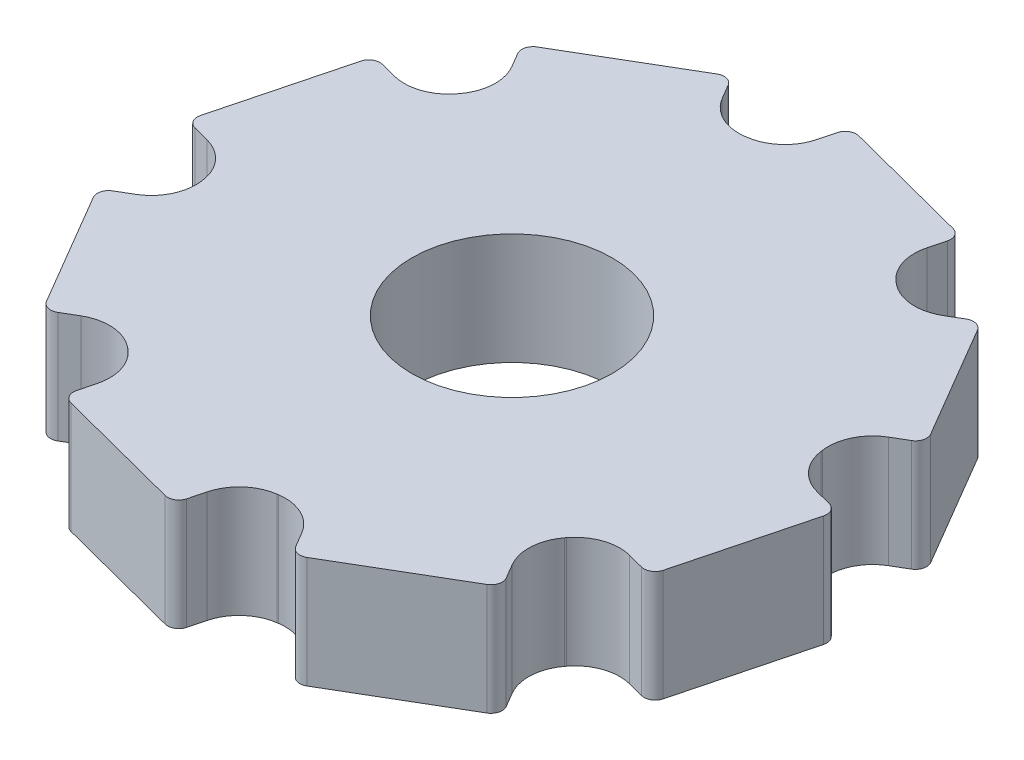
SolidWorks part; units mm, degrees
ref_plane "Спереди" through (0, 0, 0) normal (0, 0, 1) x (1, 0, 0)
ref_plane "Сверху" through (0, 0, 0) normal (0, 1, 0) x (1, 0, 0)
ref_plane "Справа" through (0, 0, 0) normal (1, 0, 0) x (0, 0, -1)
sketch "Эскиз1" plane through (0, 0, 0) normal (0, 1, 0) x (1, 0, 0)
  line L0 (-2.8067, 0.7298) -> (0, 0) construction
  line L1 (2.5044, -1.8924) -> (3.109, 0.4327) construction
  line L2 (3.109, 0.4327) -> (1.8924, 2.5044) construction
  line L3 (1.8924, 2.5044) -> (-0.4327, 3.109) construction
  line L4 (-0.4327, 3.109) -> (-2.5044, 1.8924) construction
  line L5 (-2.5044, 1.8924) -> (-3.109, -0.4327) construction
  line L6 (-3.109, -0.4327) -> (-1.8924, -2.5044) construction
  line L7 (-1.8924, -2.5044) -> (0.4327, -3.109) construction
  line L8 (0.4327, -3.109) -> (2.5044, -1.8924) construction
  line L9 (-2.9552, 0.1586) -> (-2.6581, 1.3011)
  line L10 (-2.5362, 1.3727) -> (-2.3902, 1.3347)
  line L11 (-2.8836, 0.0366) -> (-2.7376, -0.0013)
  line L12 (-0.8227, 2.764) -> (-0.7463, 2.6339)
  line L13 (-1.9775, 2.2018) -> (-0.9596, 2.7996)
  line L14 (-2.0131, 2.0649) -> (-1.9367, 1.9349)
  line L15 (1.3727, 2.5362) -> (1.3347, 2.3902)
  line L16 (0.1586, 2.9552) -> (1.3011, 2.6581)
  line L17 (0.0366, 2.8836) -> (-0.0013, 2.7376)
  line L18 (2.764, 0.8227) -> (2.6339, 0.7463)
  line L19 (2.2018, 1.9775) -> (2.7996, 0.9596)
  line L20 (2.0649, 2.0131) -> (1.9349, 1.9367)
  line L21 (2.5362, -1.3727) -> (2.3902, -1.3347)
  line L22 (2.9552, -0.1586) -> (2.6581, -1.3011)
  line L23 (2.8836, -0.0366) -> (2.7376, 0.0013)
  line L24 (0.8227, -2.764) -> (0.7463, -2.6339)
  line L25 (1.9775, -2.2018) -> (0.9596, -2.7996)
  line L26 (2.0131, -2.0649) -> (1.9367, -1.9349)
  line L27 (-1.3727, -2.5362) -> (-1.3347, -2.3902)
  line L28 (-0.1586, -2.9552) -> (-1.3011, -2.6581)
  line L29 (-0.0366, -2.8836) -> (0.0013, -2.7376)
  line L30 (-2.764, -0.8227) -> (-2.6339, -0.7463)
  line L31 (-2.2018, -1.9775) -> (-2.7996, -0.9596)
  line L32 (-2.0649, -2.0131) -> (-1.9349, -1.9367)
  arc A0 (-0.3342, 2.442) -> (-0.3454, 2.4404) centre (0, 0) ccw
  circle A1 centre (0, 0) radius 0.9
  arc A2 (-2.442, -0.3342) -> (-2.4404, -0.3454) centre (0, 0) ccw
  arc A3 (-1.9631, 1.4904) -> (-1.9699, 1.4815) centre (0, 0) ccw
  arc A4 (-1.4904, -1.9631) -> (-1.4815, -1.9699) centre (0, 0) ccw
  arc A5 (1.4904, 1.9631) -> (1.4815, 1.9699) centre (0, 0) ccw
  arc A6 (2.442, 0.3342) -> (2.4404, 0.3454) centre (0, 0) ccw
  arc A7 (1.9631, -1.4904) -> (1.9699, -1.4815) centre (0, 0) ccw
  arc A8 (0.3342, -2.442) -> (0.3454, -2.4404) centre (0, 0) ccw
  arc A9 (-1.9367, 1.9349) -> (-1.9631, 1.4904) centre (-2.2817, 1.7323) cw
  arc A10 (-1.9699, 1.4815) -> (-2.3902, 1.3347) centre (-2.2895, 1.7219) cw
  arc A11 (-2.7376, -0.0013) -> (-2.442, -0.3342) centre (-2.8383, -0.3885) cw
  arc A12 (-2.4404, -0.3454) -> (-2.6339, -0.7463) centre (-2.8365, -0.4014) cw
  arc A13 (-1.9349, -1.9367) -> (-1.4904, -1.9631) centre (-1.7323, -2.2817) cw
  arc A14 (-1.4815, -1.9699) -> (-1.3347, -2.3902) centre (-1.7219, -2.2895) cw
  arc A15 (0.0013, -2.7376) -> (0.3342, -2.442) centre (0.3885, -2.8383) cw
  arc A16 (0.3454, -2.4404) -> (0.7463, -2.6339) centre (0.4014, -2.8365) cw
  arc A17 (1.9367, -1.9349) -> (1.9631, -1.4904) centre (2.2817, -1.7323) cw
  arc A18 (1.9699, -1.4815) -> (2.3902, -1.3347) centre (2.2895, -1.7219) cw
  arc A19 (2.7376, 0.0013) -> (2.442, 0.3342) centre (2.8383, 0.3885) cw
  arc A20 (2.4404, 0.3454) -> (2.6339, 0.7463) centre (2.8365, 0.4014) cw
  arc A21 (1.9349, 1.9367) -> (1.4904, 1.9631) centre (1.7323, 2.2817) cw
  arc A22 (1.4815, 1.9699) -> (1.3347, 2.3902) centre (1.7219, 2.2895) cw
  arc A23 (-0.3342, 2.442) -> (-0.0013, 2.7376) centre (-0.3885, 2.8383) ccw
  arc A24 (-0.3454, 2.4404) -> (-0.7463, 2.6339) centre (-0.4014, 2.8365) cw
  arc A25 (0.0366, 2.8836) -> (0.1586, 2.9552) centre (0.1334, 2.8584) cw
  arc A26 (1.3727, 2.5362) -> (1.3011, 2.6581) centre (1.2759, 2.5613) ccw
  arc A27 (2.0649, 2.0131) -> (2.2018, 1.9775) centre (2.1155, 1.9269) cw
  arc A28 (2.764, 0.8227) -> (2.7996, 0.9596) centre (2.7133, 0.9089) ccw
  arc A29 (2.8836, -0.0366) -> (2.9552, -0.1586) centre (2.8584, -0.1334) cw
  arc A30 (2.5362, -1.3727) -> (2.6581, -1.3011) centre (2.5613, -1.2759) ccw
  arc A31 (1.9775, -2.2018) -> (2.0131, -2.0649) centre (1.9269, -2.1155) ccw
  arc A32 (0.9596, -2.7996) -> (0.8227, -2.764) centre (0.9089, -2.7133) cw
  arc A33 (-0.0366, -2.8836) -> (-0.1586, -2.9552) centre (-0.1334, -2.8584) cw
  arc A34 (-1.3011, -2.6581) -> (-1.3727, -2.5362) centre (-1.2759, -2.5613) cw
  arc A35 (-2.0649, -2.0131) -> (-2.2018, -1.9775) centre (-2.1155, -1.9269) cw
  arc A36 (-2.8836, 0.0366) -> (-2.9552, 0.1586) centre (-2.8584, 0.1334) cw
  arc A37 (-2.764, -0.8227) -> (-2.7996, -0.9596) centre (-2.7133, -0.9089) ccw
  arc A38 (-2.6581, 1.3011) -> (-2.5362, 1.3727) centre (-2.5613, 1.2759) cw
  arc A39 (-2.0131, 2.0649) -> (-1.9775, 2.2018) centre (-1.9269, 2.1155) cw
  arc A40 (-0.8227, 2.764) -> (-0.9596, 2.7996) centre (-0.9089, 2.7133) ccw
  point P12 (-7.6003, 1.7412)
  point P49 (0, 0)
  point P50 (-2.1163, 1.2635)
  point P53 (-2.4637, -0.0726)
  point P104 (-2.9804, 0.0618)
  point P109 (-2.6329, 1.3979)
  dimension "D1" = 8
  dimension "D2" = 0.4
  dimension "D3" = 0.1
extrude "Бобышка-Вытянуть1" add sketch "Эскиз1" along normal blind 1
